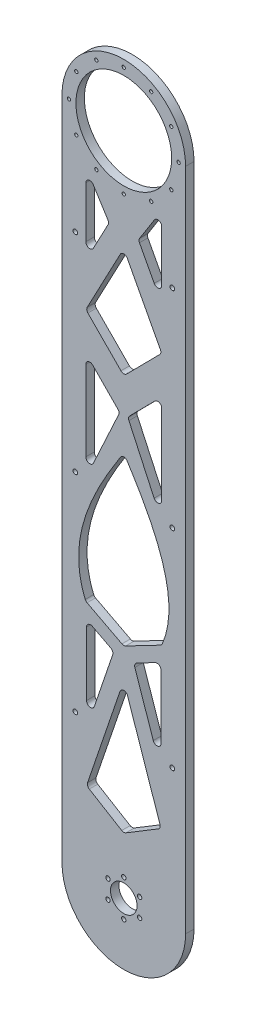
SolidWorks part; units mm, degrees
material "1060 Alloy"
ref_plane "Front Plane" through (0, 0, 0) normal (0, 0, 1) x (1, 0, 0)
ref_plane "Top Plane" through (0, 0, 0) normal (0, 1, 0) x (1, 0, 0)
ref_plane "Right Plane" through (0, 0, 0) normal (1, 0, 0) x (0, 0, -1)
sketch "Sketch2" plane through (0, 0, 0) normal (0, 0, 1) x (1, 0, 0)
  line L0 (0, 0) -> (0, 500) construction
  line L1 (-46.5, 0) -> (-46.5, 500)
  line L2 (46.5, 0) -> (46.5, 500)
  arc A0 (-46.5, 0) -> (46.5, 0) centre (0, 0) ccw
  arc A1 (46.5, 500) -> (-46.5, 500) centre (0, 500) ccw
  circle A2 centre (0, 500) radius 37.25 construction
  circle A3 centre (0, 0) radius 10
  circle A4 centre (0, 13.75) radius 1.65
  circle A5 centre (0, 0) radius 13.75 construction
  circle A6 centre (11.9078, 6.875) radius 1.65
  circle A7 centre (11.9078, -6.875) radius 1.65
  circle A8 centre (0, -13.75) radius 1.65
  circle A9 centre (-11.9078, -6.875) radius 1.65
  circle A10 centre (-11.9078, 6.875) radius 1.65
  point P3 (0, 250)
  point P27 (0, 0)
  dimension "D2" = 74.5
  dimension "D4" = 20
  dimension "D5" = 3.3
  dimension "D6" = 27.5
  dimension "D3" = 46.5
  dimension "D1" = 500
  dimension "D7" = 6
extrude "Boss-Extrude1" add sketch "Sketch2" along normal blind 6.35
sketch "Sketch4" plane through (0, 0, 6.35) normal (0, 0, 1) x (1, 0, 0)
  line L0 (0, 500) -> (0, 999.1647) construction
  line L29 (46.5, 500) -> (-46.5, 500) construction
  line L31 (28.0053, 59.376) -> (0, 42.4117)
  line L32 (0, 141.6934) -> (28.0053, 59.376)
  line L33 (-28.0053, 59.376) -> (0, 141.6934)
  line L34 (0, 42.4117) -> (-28.0053, 59.376)
  line L35 (-7.5, 156.9059) -> (-28.0053, 96.6336)
  line L36 (-28.0053, 167.5829) -> (-7.5, 156.9059)
  line L37 (-28.0053, 96.6336) -> (-28.0053, 167.5829)
  line L38 (28.0053, 167.5829) -> (7.5, 156.9059)
  line L39 (28.0053, 96.6336) -> (28.0053, 167.5829)
  line L40 (7.5, 156.9059) -> (28.0053, 96.6336)
  line L41 (0, 164.2751) -> (28.5505, 179.1412)
  line L42 (0, 164.2751) -> (-28.5505, 179.1412)
  line L43 (28.5505, 259.5868) -> (3, 314.9383)
  line L44 (28.5505, 340.7931) -> (28.5505, 259.5868)
  line L45 (3, 314.9383) -> (28.5505, 340.7931)
  line L46 (-3, 314.9383) -> (-28.5505, 340.7931)
  line L47 (-28.5505, 259.5868) -> (-3, 314.9383)
  line L48 (-28.5505, 340.7931) -> (-28.5505, 259.5868)
  line L49 (0, 423.1428) -> (-28.5505, 369.2462)
  line L50 (-28.5505, 369.2462) -> (0, 340.3557)
  line L51 (0, 340.3557) -> (28.5505, 369.2462)
  line L52 (0, 423.1428) -> (28.5505, 369.2462)
  line L53 (-28.5505, 462.0952) -> (-28.5505, 401.2902)
  line L54 (-11, 434.4215) -> (-28.5505, 462.0952)
  line L55 (-28.5505, 401.2902) -> (-11, 434.4215)
  line L56 (28.5505, 401.2902) -> (11, 434.4215)
  line L57 (28.5505, 462.0952) -> (28.5505, 401.2902)
  line L58 (11, 434.4215) -> (28.5505, 462.0952)
  arc A0 (46.5, 500) -> (-46.5, 500) centre (0, 500) ccw construction
  arc A1 (46.5, 500) -> (-46.5, 500) centre (0, 500) ccw construction
  spline S2 degree 3 poles (28.5505, 179.1412) (45.3203, 216.9857) (19.4301, 259.7903) (0, 290.0258) knots 0 0 0 0 1 1 1 1
  spline S3 degree 3 poles (-28.5505, 179.1412) (-45.3203, 216.9857) (-19.4301, 259.7903) (0, 290.0258) knots 0 0 0 0 1 1 1 1
extrude "Cut-Extrude1" cut sketch "Sketch4" against normal blind 10
fillet "Fillet3" radius 3 30 edges at (-11, 434.4215, 3.175) (-28.5505, 401.2902, 3.175) (28.5505, 401.2902, 3.175) (11, 434.4215, 3.175) (28.5505, 462.0952, 3.175) (-28.5505, 462.0952, 3.175) (0, 423.1428, 3.175) (-28.5505, 369.2462, 3.175) (28.5505, 369.2462, 3.175) (0, 340.3557, 3.175) (28.5505, 340.7931, 3.175) (-28.5505, 340.7931, 3.175) (-3, 314.9383, 3.175) (3, 314.9383, 3.175) (28.5505, 259.5868, 3.175) (-28.5505, 259.5868, 3.175) (28.5505, 179.1412, 3.175) (0, 290.0258, 3.175) (-28.5505, 179.1412, 3.175) (0, 164.2751, 3.175) (-28.0053, 96.6336, 3.175) (28.0053, 96.6336, 3.175) (7.5, 156.9059, 3.175) (-28.0053, 167.5829, 3.175) (28.0053, 167.5829, 3.175) (0, 141.6934, 3.175) (28.0053, 59.376, 3.175) (-28.0053, 59.376, 3.175) (0, 42.4117, 3.175) (-7.5, 156.9059, 3.175)
sketch "Sketch5" plane through (0, 0, 6.35) normal (0, 0, 1) x (1, 0, 0)
  line L0 (0, -46.5) -> (108.8395, -46.5) construction
  line L1 (46.5, 100) -> (-46.5, 100) construction
  line L2 (46.5, 0) -> (46.5, 500) construction
  line L3 (-46.5, 500) -> (-46.5, 0) construction
  line L4 (-46.5, 106.35) -> (46.5, 106.35) construction
  line L5 (36.5, 106.35) -> (36.5, 100) construction
  line L6 (0, 106.35) -> (0, 100) construction
  line L7 (-46.5, 256.35) -> (46.5, 256.35) construction
  line L8 (-46.5, 181.35) -> (46.5, 181.35) construction
  line L9 (-46.5, 337.7) -> (46.5, 337.7) construction
  arc A1 (-46.5, 0) -> (46.5, 0) centre (0, 0) ccw construction
  circle A2 centre (36.5, 103.175) radius 1.75
  circle A3 centre (-36.5, 103.175) radius 1.75
  circle A4 centre (36.5, 259.525) radius 1.75
  circle A5 centre (-36.5, 259.525) radius 1.75
  circle A6 centre (36.5, 415.875) radius 1.75
  circle A7 centre (-36.5, 415.875) radius 1.75
  point P18 (36.5, 103.175)
  dimension "D2" = 3.5
  dimension "D1" = 146.5
  dimension "D3" = 10
  dimension "D4" = 6.35
  dimension "D5" = 150
  dimension "D6" = 81.35
  dimension "D7" = 81.35
extrude "Cut-Extrude2" cut sketch "Sketch5" against normal through all
sketch "Sketch6" plane through (0, 0, 6.35) normal (0, 0, 1) x (1, 0, 0)
  circle A0 centre (0, 500) radius 26.5
  arc A1 (46.5, 500) -> (-46.5, 500) centre (0, 500) ccw construction
  arc A2 (46.5, 500) -> (-46.5, 500) centre (0, 500) ccw construction
  dimension "D1" = 20
extrude "Cut-Extrude3" cut sketch "Sketch6" against normal blind 10
sketch "Sketch7" plane through (0, 0, 6.35) normal (0, 0, 1) x (1, 0, 0)
  line L1 (40.0163, 523.6842) -> (44.1104, 529.9682) construction
  line L2 (23.6842, 540.0163) -> (29.9682, 544.1104) construction
  line L3 (44.1104, 529.9682) -> (29.9682, 544.1104)
  line L4 (0, 500) -> (37.0393, 537.0393) construction
  line L5 (0, 500) -> (0, 546.5) construction
  arc A0 (46.5, 500) -> (-46.5, 500) centre (0, 500) ccw construction
  arc A1 (29.9682, 544.1104) -> (16.4747, 543.4837) centre (22.4977, 559.381) cw
  arc A2 (44.1104, 529.9682) -> (43.4837, 516.4747) centre (59.381, 522.4977) ccw
  arc A3 (16.4747, 543.4837) -> (43.4837, 516.4747) centre (0, 500) cw
  dimension "D3" = 17
  dimension "D5" = 17
  dimension "D1" = 20
  dimension "D2" = 7.5
  dimension "D4" = 8
  dimension "D6" = 8
  dimension "D7" = 45
extrude "Boss-Extrude2" add sketch "Sketch7" against normal up to surface (6.35 mm away) up to face at (26.5, 500, 0)
sketch "Sketch8" plane through (287.0393, 287.0393, 0) normal (0.7071, 0.7071, 0) x (0, 0, -1)
  line L0 (0, 363.5534) -> (-6.35, 363.5534) construction
  line L1 (0, 343.5534) -> (-6.35, 343.5534) construction
  line L2 (-6.35, 343.5534) -> (-6.35, 363.5534) construction
  point P0 (-3.175, 359.5534)
  point P1 (-3.175, 347.5534)
  dimension "D1" = 4
  dimension "D2" = 4
  dimension "D3" = 3.175
hole_wizard "Tap Drill for M3x0.5 Tap1" positions "Sketch8" profile "Sketch9" hole size "M3x0.5" standard "ANSI Metric"
sketch "Sketch9" plane through (32.7967, 541.282, 3.175) normal (0, 0, 1) x (-0.7071, 0.7071, 0)
  line L0 (0, 0) -> (0, 5.7511)
  line L1 (0, 5.7511) -> (1.25, 5)
  line L2 (1.25, 5) -> (1.25, 0)
  line L5 (1.25, 0) -> (0, 0)
  line L10 (0, 5.7511) -> (-1.25, 5) construction
  line L11 (0, -6.35) -> (0, 107.95) construction
  dimension "Hole Dia." = 2.5
  dimension "Hole Depth" = 5
  dimension "Drill Angle" = 118
pattern_circular "CirPattern2" count 2 every 90 about axis through (0, 500, 0) along (0, 0, 1) of "Boss-Extrude2", "Tap Drill for M3x0.5 Tap1"
sketch "Sketch10" plane through (0, 0, 6.35) normal (0, 0, 1) x (1, 0, 0)
  line L0 (-43.4837, 516.4747) -> (-63.4837, 516.4747)
  line L1 (43.4837, 516.4747) -> (63.4837, 516.4747)
  arc A0 (43.4837, 516.4747) -> (-43.4837, 516.4747) centre (0, 500) ccw
  arc A1 (46.5, 500) -> (43.4837, 516.4747) centre (0, 500) ccw construction
  arc A2 (-63.4837, 516.4747) -> (63.4837, 516.4747) centre (0, 500) cw
  dimension "D1" = 19.0866
  dimension "D2" = 20
extrude "Cut-Extrude4" cut sketch "Sketch10" against normal through all
sketch "Sketch11" plane through (0, 0, 6.35) normal (0, 0, 1) x (1, 0, 0)
  circle A0 centre (0, 500) radius 36
  circle A1 centre (0, 500) radius 26.5 construction
  dimension "D1" = 72
extrude "Cut-Extrude5" cut sketch "Sketch11" against normal through all
sketch "Sketch12" plane through (0, 0, 6.35) normal (0, 0, 1) x (1, 0, 0)
  line L0 (0, 536) -> (0, 546.5) construction
  circle A0 centre (0, 500) radius 41.25 construction
  circle A1 centre (0, 500) radius 36 construction
  arc A2 (46.5, 500) -> (-46.5, 500) centre (0, 500) ccw construction
  circle A3 centre (0, 541.25) radius 1.25
  circle A4 centre (20.625, 535.7235) radius 1.25
  circle A5 centre (35.7235, 520.625) radius 1.25
  circle A6 centre (41.25, 500) radius 1.25
  circle A7 centre (35.7235, 479.375) radius 1.25
  circle A8 centre (20.625, 464.2765) radius 1.25
  circle A9 centre (0, 458.75) radius 1.25
  circle A10 centre (-20.625, 464.2765) radius 1.25
  circle A11 centre (-35.7235, 479.375) radius 1.25
  circle A12 centre (-41.25, 500) radius 1.25
  circle A13 centre (-35.7235, 520.625) radius 1.25
  circle A14 centre (-20.625, 535.7235) radius 1.25
  point P9 (0, 541.25)
  point P36 (0, 500)
  dimension "D1" = 2.5
  dimension "D2" = 12
extrude "Cut-Extrude6" cut sketch "Sketch12" against normal through all both and the other way through all
equation "\"L1L\"=500"
equation "\"L1Thick\"=6.35"
equation "\"D1@Sketch2\"=\"L1L\""
equation "\"Harm-Drive-Outer\"=74.5"
equation "\"D2@Sketch2\"=\"Harm-Drive-Outer\""
equation "\"D1@Boss-Extrude1\"=\"L1Thick\""
